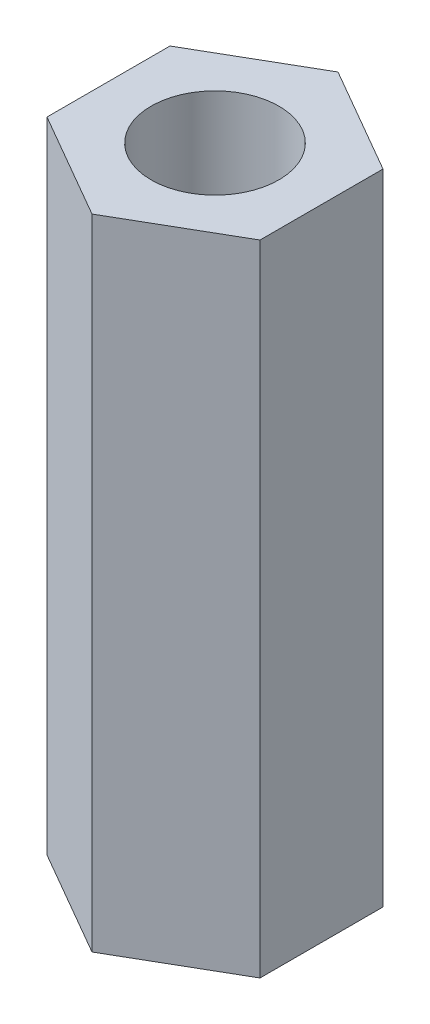
SolidWorks part; units mm, degrees
ref_plane "Plan de face" through (0, 0, 0) normal (0, 0, 1) x (1, 0, 0)
ref_plane "Plan de dessus" through (0, 0, 0) normal (0, 1, 0) x (1, 0, 0)
ref_plane "Plan de droite" through (0, 0, 0) normal (1, 0, 0) x (0, 0, -1)
sketch "Esquisse1" plane through (0, 0, 0) normal (0, 1, 0) x (1, 0, 0)
  line L0 (0, 9.7934) -> (0, -17.8331) construction
  line L1 (0, -2.8868) -> (2.5, -1.4434)
  line L2 (2.5, -1.4434) -> (2.5, 1.4434)
  line L3 (2.5, 1.4434) -> (0, 2.8868)
  line L4 (0, 2.8868) -> (-2.5, 1.4434)
  line L5 (-2.5, 1.4434) -> (-2.5, -1.4434)
  line L6 (-2.5, -1.4434) -> (0, -2.8868)
  circle A0 centre (0, 0) radius 2.5 construction
  circle A1 centre (0, 0) radius 1.5
  dimension "D1" = 5
  dimension "D2" = 3
extrude "Boss.-Extru.1" add sketch "Esquisse1" along normal blind 15
